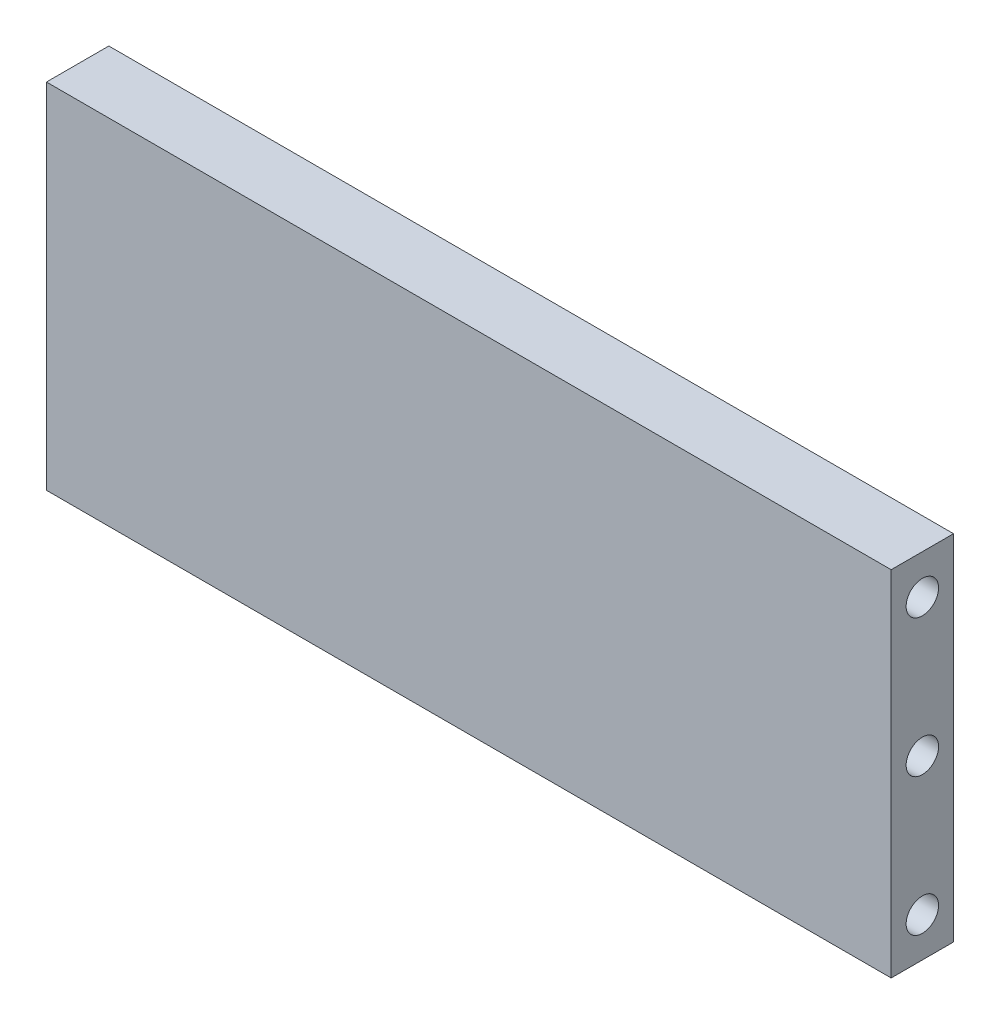
SolidWorks part; units mm, degrees
ref_plane "Front Plane" through (0, 0, 0) normal (0, 0, 1) x (1, 0, 0)
ref_plane "Top Plane" through (0, 0, 0) normal (0, 1, 0) x (1, 0, 0)
ref_plane "Right Plane" through (0, 0, 0) normal (1, 0, 0) x (0, 0, -1)
sketch "Sketch1" plane through (0, 0, 0) normal (0, 0, 1) x (1, 0, 0)
  line L1 (-43, -18) -> (43, -18)
  line L2 (-43, -18) -> (-43, 18)
  line L3 (-43, 18) -> (43, 18)
  line L4 (43, -18) -> (43, 18)
  line L5 (-43, -18) -> (43, 18) construction
  line L6 (-43, 18) -> (43, -18) construction
  point P0 (0, 0)
  dimension "D1" = 36
  dimension "D2" = 86
extrude "Boss-Extrude1" add sketch "Sketch1" along normal mid plane 6.35
sketch "Sketch2" plane through (-43, 0, 0) normal (-1, 0, 0) x (0, 0, 1)
  line L0 (0, 14) -> (0, -14) construction
  circle A0 centre (0, 14) radius 1.65
  circle A1 centre (0, -14) radius 1.65
  circle A2 centre (0, 0) radius 1.65
  point P4 (0, 0)
  point P9 (0, 0)
  dimension "D1" = 3.3
  dimension "D2" = 3.3
  dimension "D3" = 3.3
  dimension "D4" = 28
extrude "Cut-Extrude1" cut sketch "Sketch2" against normal blind 10 contours A1 | A2 | A0
mirror "Mirror1" about plane through (0, 0, 0) normal (1, 0, 0) of "Cut-Extrude1"
